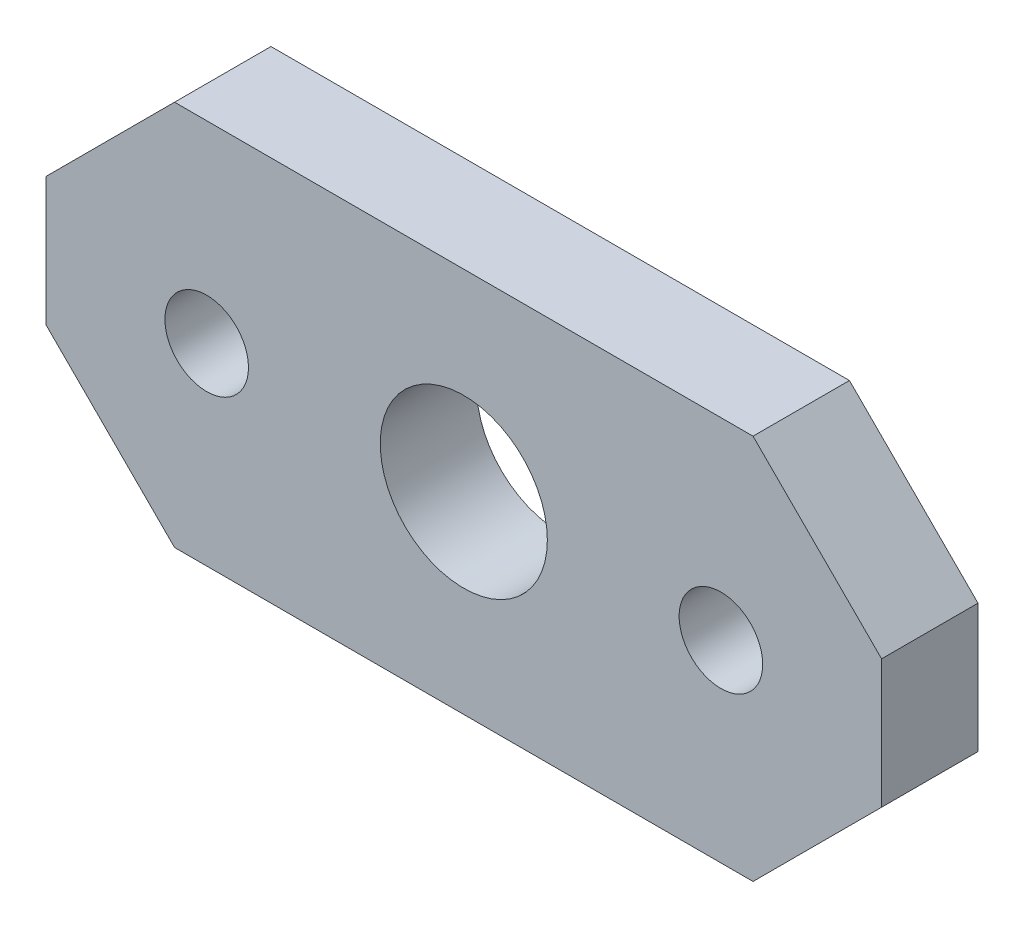
SolidWorks part; units mm, degrees
ref_plane "前视基准面" through (0, 0, 0) normal (0, 0, 1) x (1, 0, 0)
ref_plane "上视基准面" through (0, 0, 0) normal (0, 1, 0) x (1, 0, 0)
ref_plane "右视基准面" through (0, 0, 0) normal (1, 0, 0) x (0, 0, -1)
other "Configuration Table"
sketch "草图1" plane through (0, 0, 0) normal (0, 0, 1) x (1, 0, 0)
  line L0 (-9, -6) -> (9, -6)
  line L1 (9, -6) -> (13, -2)
  line L2 (13, -2) -> (13, 2)
  line L3 (13, 2) -> (9, 6)
  line L4 (9, 6) -> (-9, 6)
  line L5 (-9, 6) -> (-13, 2)
  line L6 (-13, 2) -> (-13, -2)
  line L7 (-13, -2) -> (-9, -6)
  circle A0 centre (0, 0) radius 2.6
  circle A1 centre (-8, 0) radius 1.3
  circle A2 centre (8, 0) radius 1.3
extrude "M5转接毂_双M2p5折叠轴孔" add sketch "草图1" along normal blind 3
